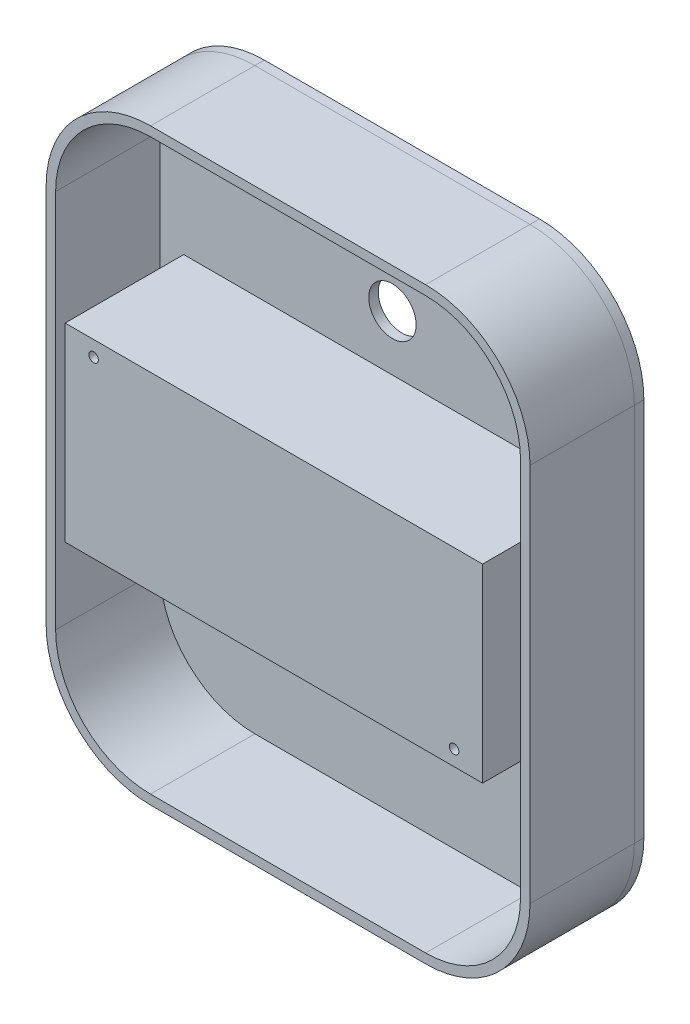
SolidWorks part; units mm, degrees
ref_plane "Front Plane" through (0, 0, 0) normal (0, 0, 1) x (1, 0, 0)
ref_plane "Top Plane" through (0, 0, 0) normal (0, 1, 0) x (1, 0, 0)
ref_plane "Right Plane" through (0, 0, 0) normal (1, 0, 0) x (0, 0, -1)
sketch "Sketch1" plane through (0, 0, 0) normal (0, 0, 1) x (1, 0, 0)
  line L0 (0, 60) -> (0, -60) construction
  line L5 (-29, 60) -> (29, 60)
  line L6 (-49, 40) -> (-49, -40)
  line L7 (-29, -60) -> (29, -60)
  line L8 (49, 40) -> (49, -40)
  line L9 (-49, 0) -> (49, 0) construction
  line L10 (-29, 62) -> (29, 62)
  line L11 (51, 40) -> (51, -40)
  line L12 (-29, -62) -> (29, -62)
  line L13 (-51, 40) -> (-51, -40)
  arc A2 (49, 40) -> (29, 60) centre (29, 40) ccw
  arc A3 (49, -40) -> (29, -60) centre (29, -40) cw
  arc A4 (-29, -60) -> (-49, -40) centre (-29, -40) cw
  arc A5 (-49, 40) -> (-29, 60) centre (-29, 40) cw
  arc A6 (51, 40) -> (29, 62) centre (29, 40) ccw
  arc A7 (51, -40) -> (29, -62) centre (29, -40) cw
  arc A8 (-29, -62) -> (-51, -40) centre (-29, -40) cw
  arc A9 (-51, 40) -> (-29, 62) centre (-29, 40) cw
  point P13 (0, 0)
  point P14 (0, 0)
  point P17 (49, 60)
  point P21 (0, 0)
  point P23 (-49, -60)
  point P26 (-49, 60)
  dimension "D5" = 20
  dimension "D3" = 98
  dimension "D4" = 120
  dimension "D6" = 2
extrude "Boss-Extrude1" add sketch "Sketch1" along normal blind 22
sketch "Sketch3" plane through (0, 0, 0) normal (0, 0, 1) x (1, 0, 0)
  line L0 (-44, -20) -> (-44, 20)
  line L1 (-44, -20) -> (44, -20)
  line L2 (44, -20) -> (44, 20)
  line L3 (-44, 20) -> (44, 20)
  line L4 (-44, 0) -> (44, 0) construction
  line L5 (0, 20) -> (0, -20) construction
  line L6 (-38, 16.75) -> (-38, 0) construction
  line L7 (38, -16.75) -> (38, 0) construction
  line L8 (-38, 16.75) -> (0, 16.75) construction
  line L9 (38, -16.75) -> (0, -16.75) construction
  circle A3 centre (-38, 16.75) radius 1
  circle A4 centre (38, -16.75) radius 1
  dimension "D5" = 2
  dimension "D1" = 88
  dimension "D2" = 40
  dimension "D3" = 76
  dimension "D4" = 33.5
extrude "Boss-Extrude2" add sketch "Sketch3" along normal blind 25
sketch "Sketch6" plane through (0, 0, 0) normal (0, 0, 1) x (1, 0, 0)
  line L0 (-29, 62) -> (29, 62)
  line L1 (51, 40) -> (51, -40)
  line L2 (-29, -62) -> (29, -62)
  line L3 (-51, 40) -> (-51, -40)
  arc A0 (51, 40) -> (29, 62) centre (29, 40) ccw
  arc A1 (51, -40) -> (29, -62) centre (29, -40) cw
  arc A2 (-29, -62) -> (-51, -40) centre (-29, -40) cw
  arc A3 (-51, 40) -> (-29, 62) centre (-29, 40) cw
  circle A4 centre (0, 41) radius 1.75
  circle A5 centre (0, -41) radius 1.75
  circle A6 centre (0, 31.6596) radius 5
  circle A7 centre (0, -30.7551) radius 5
  point P20 (0, 0)
  point P22 (0, 0)
  point P23 (0, 0)
  point P24 (0, 0)
  point P26 (-8.4291, 31.6596)
  dimension "D2" = 3.5
  dimension "D3" = 10
  dimension "D1" = 82
extrude "Boss-Extrude3" add sketch "Sketch6" against normal blind 2
sketch "Sketch4" plane through (0, 0, 0) normal (0, 0, 1) x (1, 0, 0)
  line L1 (-37.5, 55) -> (37.5, 55)
  line L2 (-37.5, 55) -> (-37.5, -55)
  line L3 (-37.5, -55) -> (37.5, -55)
  line L4 (37.5, 55) -> (37.5, -55)
  point P4 (-37.5, 0)
  point P6 (0, 55)
  dimension "D1" = 75
  dimension "D2" = 110
